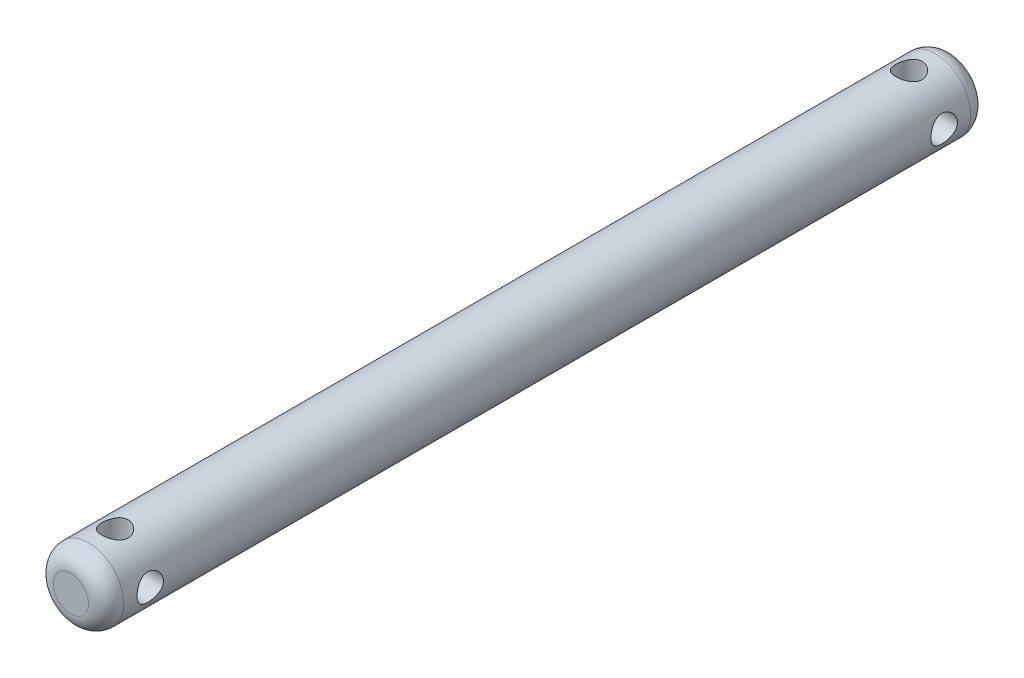
SolidWorks part; units mm, degrees
ref_plane "Front Plane" through (0, 0, 0) normal (0, 0, 1) x (1, 0, 0)
ref_plane "Top Plane" through (0, 0, 0) normal (0, 1, 0) x (1, 0, 0)
ref_plane "Right Plane" through (0, 0, 0) normal (1, 0, 0) x (0, 0, -1)
sketch "Sketch1" plane through (0, 0, 0) normal (0, 0, 1) x (1, 0, 0)
  circle A0 centre (0, 0) radius 4
extrude "Boss-Extrude1" add sketch "Sketch1" along normal mid plane 100
sketch "Sketch2" plane through (0, 0, 0) normal (1, 0, 0) x (0, 0, -1)
  line L0 (-50, 4) -> (-50, -4) construction
  line L2 (50, -4) -> (50, 4) construction
  circle A0 centre (-45, 0) radius 1.5
  circle A1 centre (45, 0) radius 1.5
  dimension "D1" = 5
  dimension "D2" = 5
extrude "Cut-Extrude1" cut sketch "Sketch2" along normal blind 5
fillet "Fillet1" radius 2 2 edges at (4, 0, -50) (4, 0, 50)
sketch "Sketch3" plane through (0, 0, 0) normal (0, 1, 0) x (1, 0, 0)
  line L0 (2, 50) -> (-2, 50) construction
  line L3 (-2, -50) -> (2, -50) construction
  circle A0 centre (0, 45) radius 1.5
  circle A1 centre (0, -45) radius 1.5
  dimension "D1" = 5
  dimension "D2" = 5
extrude "Cut-Extrude2" cut sketch "Sketch3" along normal blind 4
